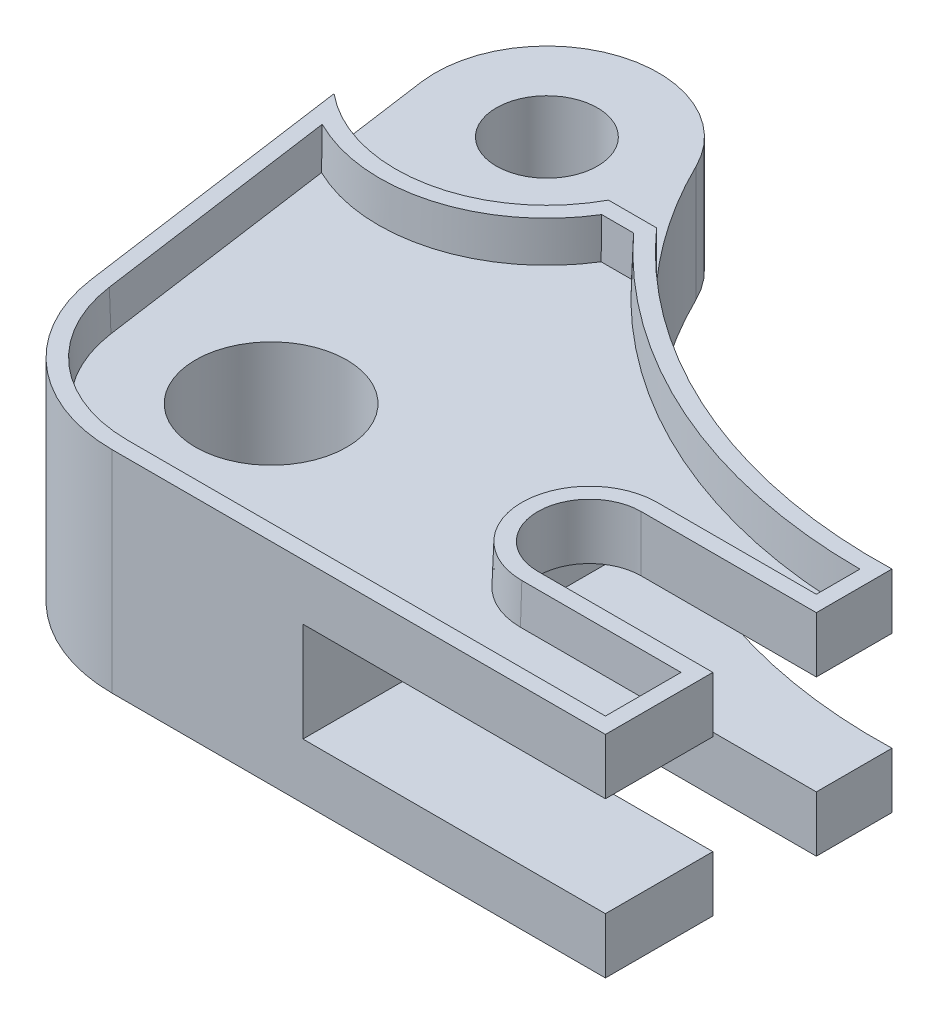
SolidWorks part; units mm, degrees
material "AISI 1020"
ref_plane "Front Plane" through (0, 0, 0) normal (0, 0, 1) x (1, 0, 0)
ref_plane "Top Plane" through (0, 0, 0) normal (0, 1, 0) x (1, 0, 0)
ref_plane "Right Plane" through (0, 0, 0) normal (1, 0, 0) x (0, 0, -1)
other "AISI"
sketch "Sketch1" plane through (0, 0, 0) normal (0, 1, 0) x (1, 0, 0)
  line L0 (0, 0) -> (-62, 0)
  line L1 (-62, 0) -> (-62, 20) construction
  line L2 (-62, 20) -> (-62, 43.1453) construction
  line L3 (-62, 20) -> (-74.6821, 67.3304) construction
  line L4 (-88.547, 65.39) -> (-81.807, 17.2281)
  line L5 (0, 36) -> (0, 103) construction
  line L6 (-22, 26.5) -> (0, 26.5)
  line L7 (-22, 13.5) -> (0, 13.5)
  line L8 (0, 0) -> (0, 13.5)
  line L9 (0, 26.5) -> (0, 36)
  circle A0 centre (-62, 20) radius 9.5
  circle A1 centre (-74.6821, 67.3304) radius 6.35
  arc A2 (-81.807, 17.2281) -> (-62, 0) centre (-62, 20) ccw
  arc A3 (-62.1103, 73.4906) -> (-88.547, 65.39) centre (-74.6821, 67.3304) ccw
  arc A4 (-22, 26.5) -> (-22, 13.5) centre (-22, 20) ccw
  arc A5 (-62.1103, 73.4906) -> (0, 36) centre (-1.945, 102.9718) ccw
  point P13 (0, 20)
  dimension "D3" = 19
  dimension "D6" = 12.7
  dimension "D7" = 28
  dimension "D8" = 20
  dimension "D10" = 6.5
  dimension "D17" = 134
  dimension "D1" = 62
  dimension "D2" = 20
  dimension "D4" = 15
  dimension "D5" = 49
  dimension "D9" = 22
  dimension "D11" = 36
  dimension "D12" = 13.5
  dimension "D13" = 26.5
  dimension "D14" = 22
  dimension "D15" = 9.5
  dimension "D16" = 67
extrude "Boss-Extrude1" add sketch "Sketch1" along normal mid plane 26.5
sketch "Sketch2" plane through (0, 0, 0) normal (1, 0, 0) x (0, 0, -1)
  line L0 (0, 13.25) -> (0, -13.25) construction
  line L7 (0, -6.25) -> (0, 6.25)
  line L8 (0, 6.25) -> (73.3389, 6.25)
  line L9 (73.3389, 6.25) -> (73.3389, -6.25)
  line L10 (73.3389, -6.25) -> (0, -6.25)
  line L11 (0, -13.25) -> (13.5, -13.25) construction
  line L12 (0, 13.25) -> (13.5, 13.25) construction
  dimension "D1" = 7
  dimension "D2" = 7
  dimension "D3" = 73.3389
extrude "Cut-Extrude3" cut sketch "Sketch2" against normal blind 38 contours L8 L9 L10 L7
sketch "Sketch3" plane through (0, 13.25, 0) normal (0, 1, 0) x (1, 0, 0)
  line L0 (-88.547, 65.39) -> (-81.807, 17.2281) construction
  line L1 (-57.9489, 58.3304) -> (-51.9064, 58.3304)
  arc A0 (-57.9489, 58.3304) -> (-86.7667, 52.6688) centre (-74.6821, 67.3304) cw
  arc A1 (-62.1103, 73.4906) -> (0, 36) centre (-1.945, 102.9718) ccw construction
  dimension "D1" = 19
  dimension "D2" = 9
extrude "Cut-Extrude5" cut sketch "Sketch3" against normal blind 6 and the other way through all
sketch "Sketch4" plane through (0, -13.25, 0) normal (0, -1, 0) x (1, 0, 0)
  line L0 (-88.547, -65.39) -> (-81.807, -17.2281) construction
  line L1 (-57.9489, -58.3304) -> (-51.9064, -58.3304)
  arc A0 (-57.9489, -58.3304) -> (-86.7667, -52.6688) centre (-74.6821, -67.3304) ccw
  arc A1 (0, -36) -> (-62.1103, -73.4906) centre (-1.945, -102.9718) ccw construction
  dimension "D1" = 19
  dimension "D2" = 9
extrude "Cut-Extrude6" cut sketch "Sketch4" against normal blind 6 and the other way through all flip side to cut
sketch "Sketch6" plane through (0, 13.25, 0) normal (0, 1, 0) x (1, 0, 0)
  line L14 (-2, 28.5) -> (-2, 33.9718)
  line L15 (-22, 28.5) -> (-2, 28.5)
  line L16 (-2, 11.5) -> (-22, 11.5)
  line L17 (-2, 2) -> (-2, 11.5)
  line L18 (-62, 2) -> (-2, 2)
  line L19 (-84.1778, 48.5999) -> (-79.8263, 17.5053)
  line L20 (-52.7936, 56.3304) -> (-56.7936, 56.3304)
  line L21 (-2, 28.5) -> (-2, 33.9718)
  line L22 (-22, 28.5) -> (-2, 28.5)
  line L23 (-2, 11.5) -> (-22, 11.5)
  line L24 (-2, 2) -> (-2, 11.5)
  line L25 (-62, 2) -> (-2, 2)
  line L26 (-84.1778, 48.5999) -> (-79.8263, 17.5053)
  line L27 (-52.7936, 56.3304) -> (-56.7936, 56.3304)
  arc A8 (-22, 28.5) -> (-22, 11.5) centre (-22, 20) ccw
  arc A9 (-79.8263, 17.5053) -> (-62, 2) centre (-62, 20) ccw
  arc A10 (-84.1778, 48.5999) -> (-56.7936, 56.3304) centre (-74.6821, 67.3304) ccw
  arc A11 (-52.7936, 56.3304) -> (-2, 33.9718) centre (-1.945, 102.9718) ccw
  arc A12 (-22, 28.5) -> (-22, 11.5) centre (-22, 20) ccw
  arc A13 (-79.8263, 17.5053) -> (-62, 2) centre (-62, 20) ccw
  arc A14 (-84.1778, 48.5999) -> (-56.7936, 56.3304) centre (-74.6821, 67.3304) ccw
  arc A15 (-52.7936, 56.3304) -> (-2, 33.9718) centre (-1.945, 102.9718) ccw
  dimension "D1" = 2
extrude "Cut-Extrude8" cut sketch "Sketch6" against normal blind 5 draft 2
mirror "Mirror8" about plane through (0, 0, 0) normal (0, 1, 0) of "Cut-Extrude8"
equation "\"A\"= 62mm"
equation "\"B\"= 20mm"
equation "\"C\"= 26.50mm"
